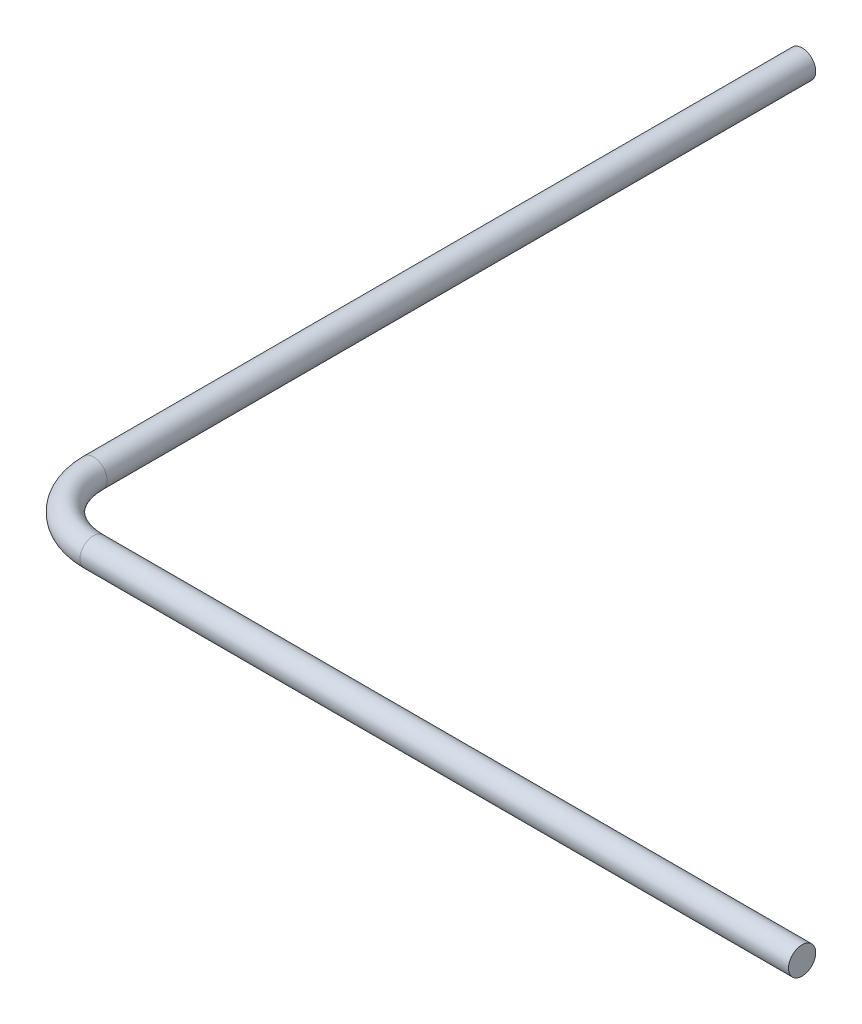
SolidWorks part; units mm, degrees
ref_plane "正面" through (0, 0, 0) normal (0, 0, 1) x (1, 0, 0)
ref_plane "平面" through (0, 0, 0) normal (0, 1, 0) x (1, 0, 0)
ref_plane "右側面" through (0, 0, 0) normal (1, 0, 0) x (0, 0, -1)
sketch "ｽｹｯﾁ1" plane through (0, 0, 0) normal (0, 0, 1) x (1, 0, 0)
  circle A0 centre (0, 0) radius 1
  dimension "D1" = 2
extrude "ﾎﾞｽ - 押し出し1" add sketch "ｽｹｯﾁ1" along normal blind 50
sketch "ｽｹｯﾁ2" plane through (0, 0, 0) normal (0, 1, 0) x (1, 0, 0)
  line L0 (0, -50) -> (0, -52)
  line L1 (-1, -50) -> (1, -50) construction
  line L2 (5, -57) -> (57, -57)
  arc A0 (0, -52) -> (5, -57) centre (5, -52) ccw
  dimension "D1" = 5
  dimension "D2" = 2
  dimension "D3" = 52
sketch "ｽｹｯﾁ3" plane through (0, 0, 50) normal (0, 0, 1) x (1, 0, 0)
  circle A1 centre (0, 0) radius 1
  circle A2 centre (0, 0) radius 1
  dimension "D1" = 0
sweep "ｽｲｰﾌﾟ1" add profiles "ｽｹｯﾁ3" path "ｽｹｯﾁ2"
